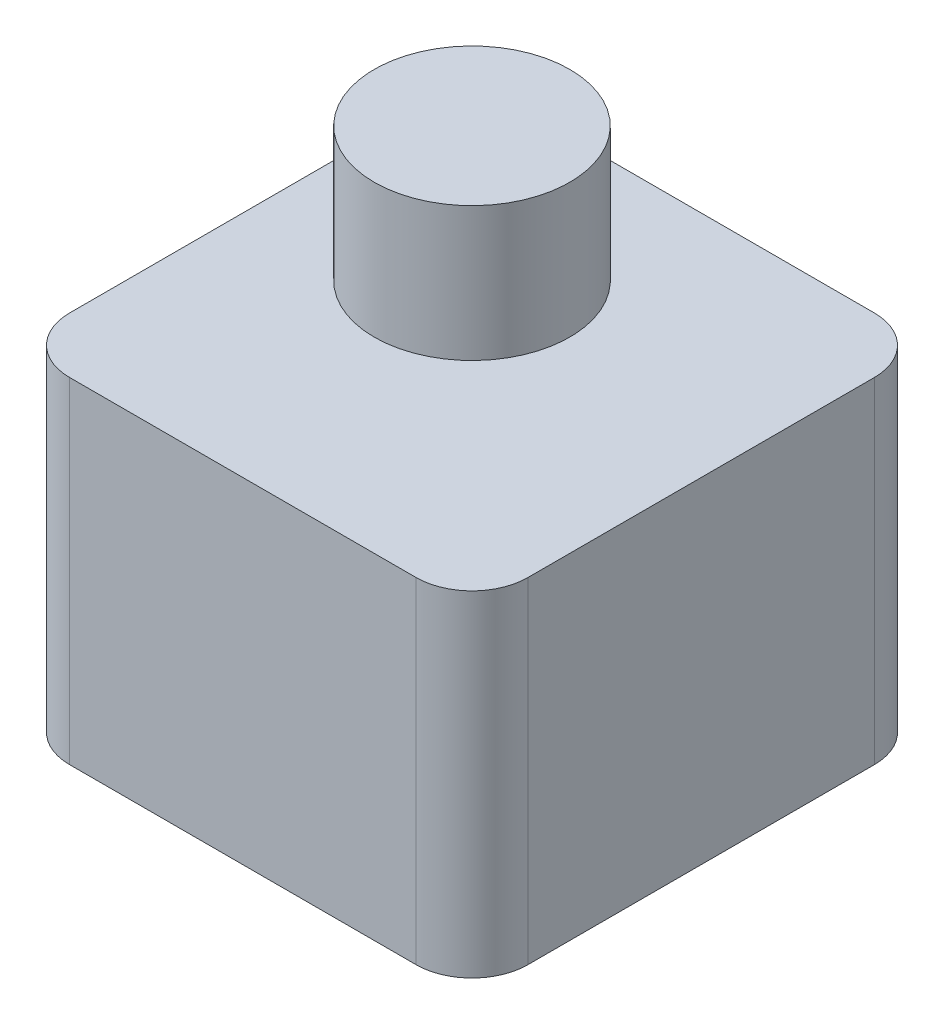
SolidWorks part; units mm, degrees
ref_plane "Alzado" through (0, 0, 0) normal (0, 0, 1) x (1, 0, 0)
ref_plane "Planta" through (0, 0, 0) normal (0, 1, 0) x (1, 0, 0)
ref_plane "Vista lateral" through (0, 0, 0) normal (1, 0, 0) x (0, 0, -1)
sketch "Croquis2" plane through (0, 0, 0) normal (0, 1, 0) x (1, 0, 0)
  line L1 (5, 41) -> (36, 41)
  line L2 (0, 36) -> (0, 5)
  line L3 (5, 0) -> (36, 0)
  line L4 (41, 36) -> (41, 5)
  arc A0 (0, 5) -> (5, 0) centre (5, 5) ccw
  arc A1 (36, 0) -> (41, 5) centre (36, 5) ccw
  arc A2 (36, 41) -> (41, 36) centre (36, 36) cw
  arc A3 (5, 41) -> (0, 36) centre (5, 36) ccw
  dimension "D1" = 5
  dimension "D2" = 41
  dimension "D3" = 41
extrude "Saliente-Extruir2" add sketch "Croquis2" along normal blind 30
sketch "Croquis3" plane through (0, 30, 0) normal (0, 1, 0) x (1, 0, 0)
  circle A3 centre (20.5, 20.5) radius 1.5
extrude "Saliente-Extruir3" add sketch "Croquis3" along normal blind 17 separate body
ref_plane "Plano2" through (0, 35, 0) normal (0, 1, 0) x (1, 0, 0)
sketch "Croquis6" plane through (0, 35, 0) normal (0, 1, 0) x (1, 0, 0)
  circle A0 centre (20.5, 20.5) radius 8.75
  dimension "D1" = 17.5
extrude "Saliente-Extruir4" add sketch "Croquis6" along normal blind 12
